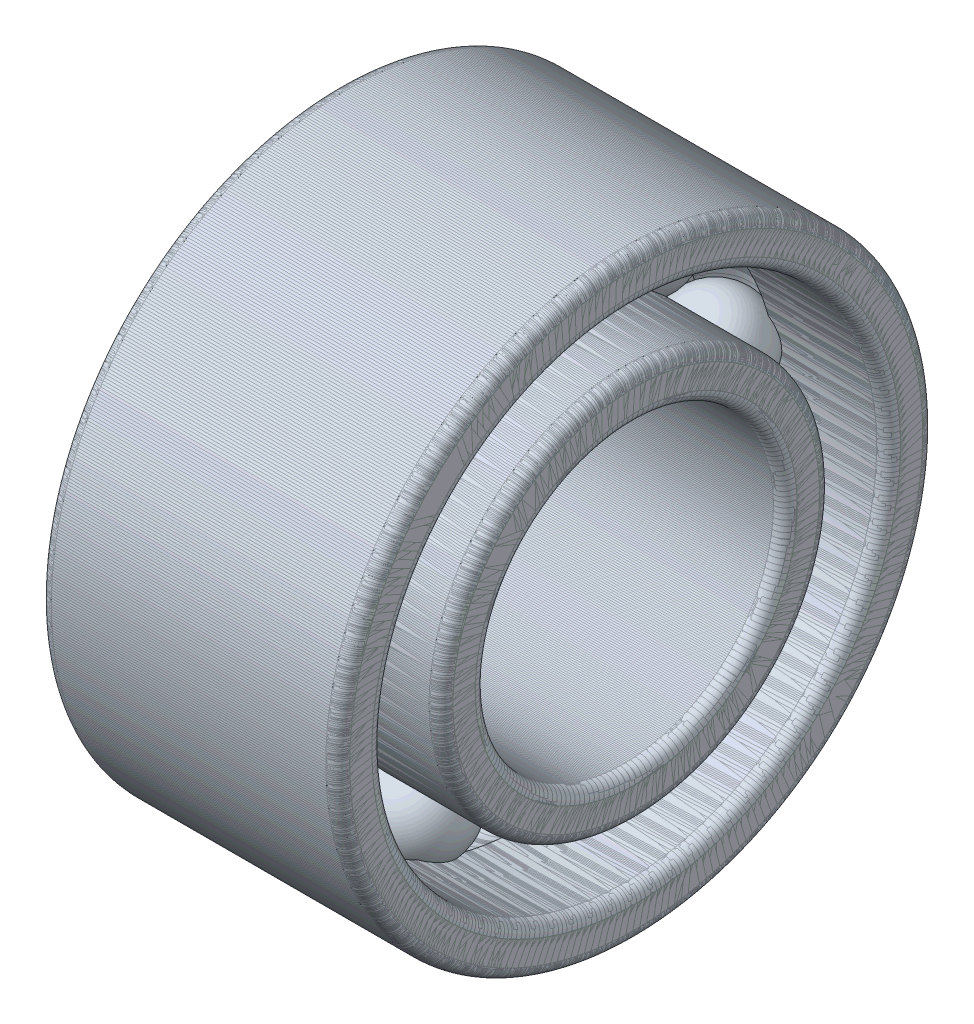
SolidWorks part; units mm, degrees
ref_plane "Front Plane" through (0, 0, 0) normal (0, 0, 1) x (1, 0, 0)
ref_plane "Top Plane" through (0, 0, 0) normal (0, 1, 0) x (1, 0, 0)
ref_plane "Right Plane" through (0, 0, 0) normal (1, 0, 0) x (0, 0, -1)
sketch "Sketch1" plane through (0, 0, 0) normal (1, 0, 0) x (0, 0, -1)
  circle A0 centre (0, 0) radius 31.75
  circle A1 centre (0, 0) radius 23.8125
  circle A2 centre (0, 0) radius 15.875
  circle A3 centre (0, 0) radius 26.8605
  circle A4 centre (0, 0) radius 20.765
  dimension "D1" = 63.5
  dimension "D2" = 53.721
  dimension "D3" = 47.625
  dimension "D4" = 41.53
  dimension "D5" = 31.75
extrude "Boss-Extrude1" add sketch "Sketch1" along normal mid plane 31.75 contours A0 A3 | A4 A2
fillet "Fillet1" radius 1.27 4 edges at (15.875, 0, -26.8605) (15.875, 0, -31.75) (-15.875, 0, -26.8605) (-15.875, 0, -31.75)
fillet "Fillet2" radius 1.27 4 edges at (15.875, 0, -20.765) (15.875, 0, -15.875) (-15.875, 0, -20.765) (-15.875, 0, -15.875)
sketch "Sketch2" plane through (0, 0, 0) normal (0, 0, 1) x (1, 0, 0)
  line L0 (0, 0) -> (26.3886, 0) construction
  circle A0 centre (0, 23.813) radius 5.08
  dimension "D1" = 10.16
  dimension "D2" = 23.813
revolve "Cut-Revolve1" cut sketch "Sketch2" angle 360 about L0
sketch "Sketch3" plane through (0, 0, 0) normal (0, 0, 1) x (1, 0, 0)
  line L0 (0.792, 28.893) -> (0.792, 18.733)
  arc A0 (0.792, 28.893) -> (0.792, 18.733) centre (0.792, 23.813) ccw
  point P1 (-4.288, 23.813)
  dimension "D1" = 5.08
  dimension "D2" = 23.813
revolve "Revolve1" add sketch "Sketch3" angle 360 about L0
pattern_circular "CirPattern1" count 9 over 360 about axis through (0, 0, 0) along (1, 0, 0) of bodies 105
